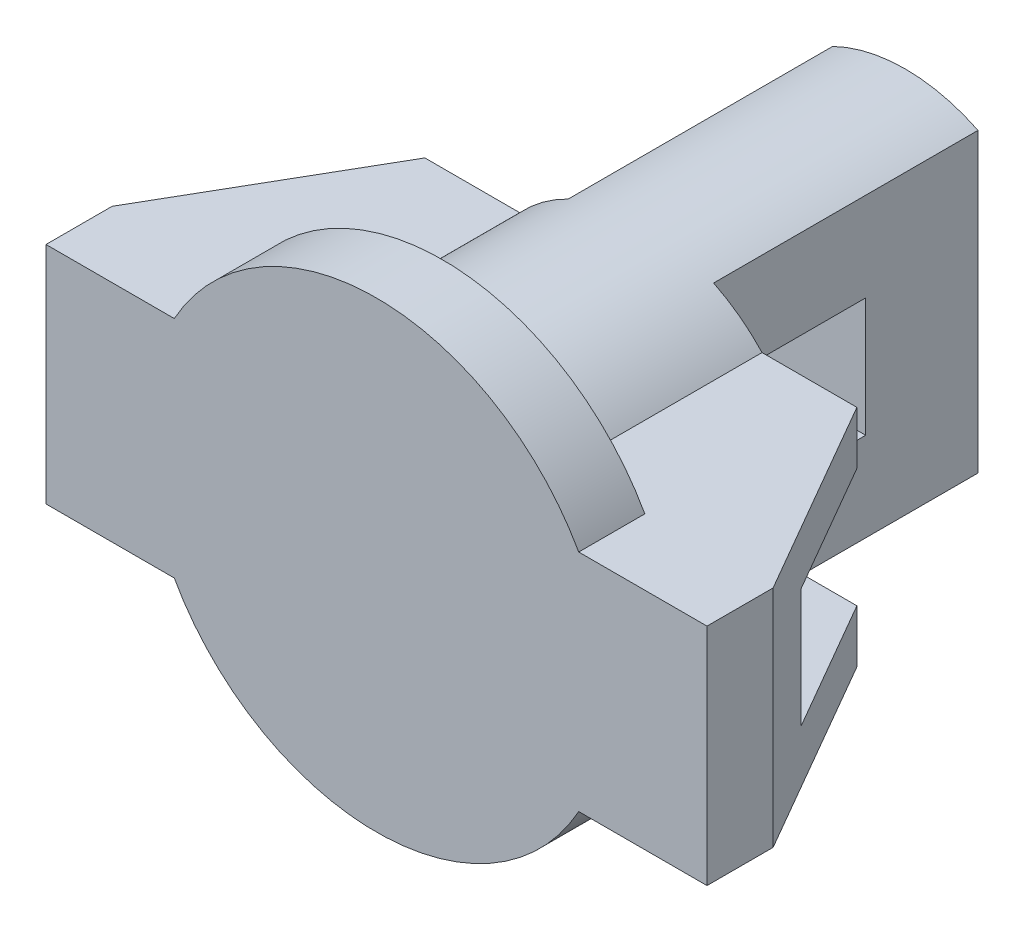
SolidWorks part; units mm, degrees
ref_plane "Front Plane" through (0, 0, 0) normal (0, 0, 1) x (1, 0, 0)
ref_plane "Top Plane" through (0, 0, 0) normal (0, 1, 0) x (1, 0, 0)
ref_plane "Right Plane" through (0, 0, 0) normal (1, 0, 0) x (0, 0, -1)
sketch "Sketch1" plane through (0, 0, 0) normal (0, 1, 0) x (1, 0, 0)
  line L0 (50, 0) -> (-50, 0)
  line L1 (-50, 0) -> (-50, 10)
  line L2 (-50, 10) -> (-32.6795, 40)
  line L3 (-32.6795, 40) -> (32.6795, 40)
  line L4 (32.6795, 40) -> (50, 10)
  line L5 (50, 10) -> (50, 0)
  point P5 (0, 0)
  point P8 (0, 0)
  point P9 (2.9031, 0)
  dimension "D1" = 100
  dimension "D2" = 10
  dimension "D3" = 10
  dimension "D4" = 50
  dimension "D5" = 40
  dimension "D6" = 150
  dimension "D7" = 150
  dimension "D8" = 40
extrude "Boss-Extrude1" add sketch "Sketch1" along normal blind 34
sketch "Sketch2" plane through (0, 0, 0) normal (0, 0, 1) x (1, 0, 0)
  circle A0 centre (0, 17) radius 35
extrude "Boss-Extrude2" add sketch "Sketch2" against normal blind 10
sketch "Sketch3" plane through (0, 0, 0) normal (0, 0, 1) x (1, 0, 0)
  circle A0 centre (0, 17) radius 25
extrude "Boss-Extrude3" add sketch "Sketch3" against normal blind 80
sketch "Sketch5" plane through (0, 0, -80) normal (0, 0, -1) x (-1, 0, 0)
  line L2 (-11, -18) -> (-11, 52)
  line L4 (11, -18) -> (11, 52)
  line L7 (-11, -18) -> (-25, -18)
  line L8 (-11, -18) -> (-11, 52)
  line L9 (-11, 52) -> (-25, 52)
  line L10 (-25, -18) -> (-25, 52)
  line L11 (11, 52) -> (25, 52)
  line L12 (11, 52) -> (11, -18)
  line L13 (11, -18) -> (25, -18)
  line L14 (25, 52) -> (25, -18)
  point P0 (0, 17)
  circle M10 centre (0, 17) radius 25
  dimension "D1" = 22
  dimension "D2" = 70
  dimension "D3" = 14
  dimension "D4" = 14
extrude "Cut-Extrude2" cut sketch "Sketch5" against normal up to surface (40 mm away) contours L2 M10 | L10 L2 L9 M10 | L10 L7 L2 M10 | L14 L4 L13 M10 | L4 M10 | L14 L11 L4 M10 up to face at (27.1723, 17, -40)
sketch "Sketch11" plane through (-11, 0, 0) normal (-1, 0, 0) x (0, 0, 1)
  line L0 (-40, 0) -> (-10, 0) construction
  line L1 (-63, 8) -> (-20, 8)
  line L2 (-63, 8) -> (-63, 26)
  line L3 (-63, 26) -> (-20, 26)
  line L4 (-20, 8) -> (-20, 26)
  line L5 (-80, 39.4499) -> (-80, -5.4499) construction
  dimension "D1" = 18
  dimension "D2" = 8
  dimension "D3" = 17
  dimension "D4" = 43
extrude "Cut-Extrude5" cut sketch "Sketch11" against normal through all and the other way through all
